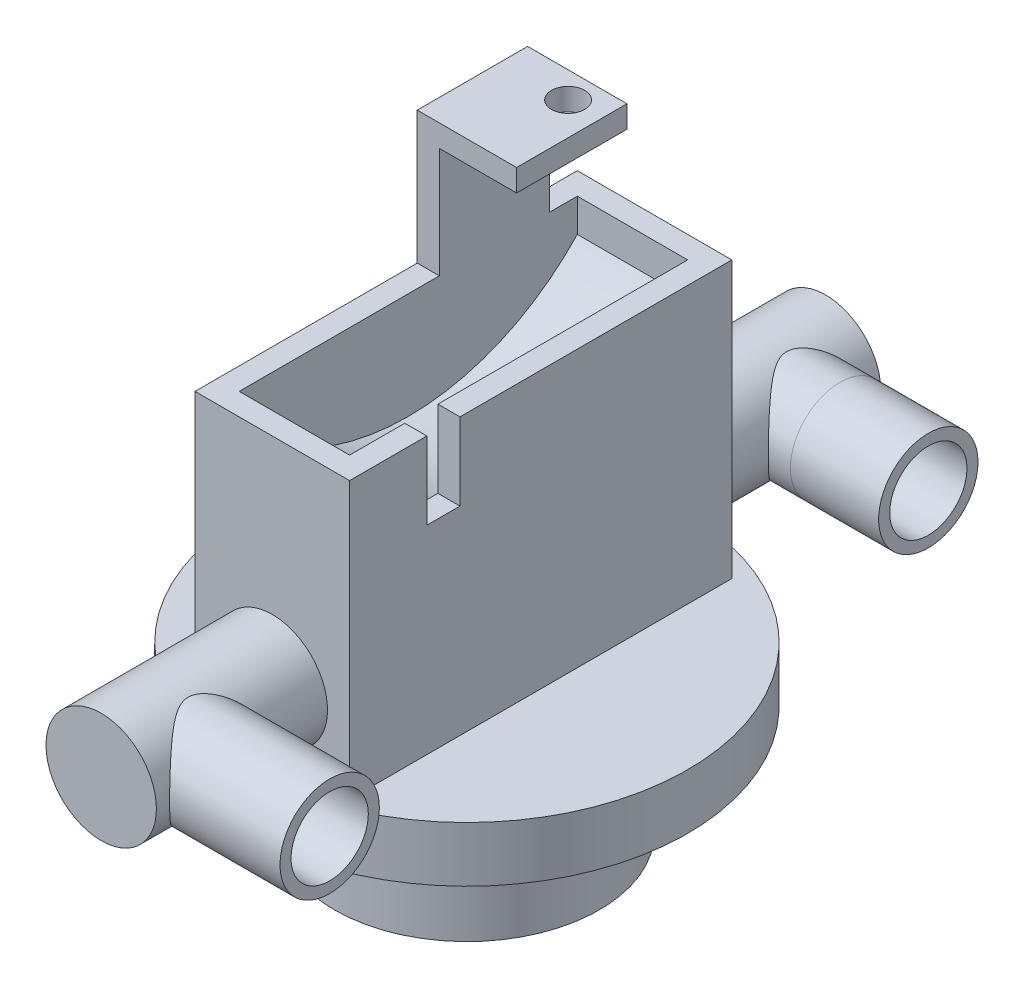
SolidWorks part; units mm, degrees
ref_plane "Спереди" through (0, 0, 0) normal (0, 0, 1) x (1, 0, 0)
ref_plane "Сверху" through (0, 0, 0) normal (0, 1, 0) x (1, 0, 0)
ref_plane "Справа" through (0, 0, 0) normal (1, 0, 0) x (0, 0, -1)
sketch "Эскиз1" plane through (0, 0, 0) normal (0, 1, 0) x (1, 0, 0)
  circle A0 centre (0, 0) radius 20
extrude "Бобышка-Вытянуть1" add sketch "Эскиз1" along normal blind 5 contours A0
sketch "Эскиз2" plane through (0, 5, 0) normal (0, 1, 0) x (1, 0, 0)
  line L0 (0, 20) -> (0, -20) construction
  line L1 (-20, 0) -> (20, 0) construction
  line L3 (-7, 17) -> (7, 17)
  line L4 (-7, 17) -> (-7, -17.63)
  line L5 (-7, -17.63) -> (7, -17.63)
  line L6 (7, 17) -> (7, -17.63)
  circle A0 centre (0, 0) radius 20 construction
  dimension "D1" = 7
  dimension "D2" = 14
  dimension "D3" = 17
  dimension "D4" = 7
  dimension "D5" = 20
extrude "Бобышка-Вытянуть2" add sketch "Эскиз2" along normal blind 25
sketch "Эскиз3" plane through (0, 30, 0) normal (0, 1, 0) x (1, 0, 0)
  line L0 (0, 17) -> (0, -17.63) construction
  line L1 (7, 17) -> (-7, 17) construction
  line L2 (-7, -17.63) -> (7, -17.63) construction
  line L3 (-7, -0.315) -> (7, -0.315) construction
  line L4 (-7, 17) -> (-7, -17.63) construction
  line L5 (7, -17.63) -> (7, 17) construction
  line L6 (-7, 17) -> (7, -17.63) construction
  line L7 (7, 17) -> (-7, -17.63) construction
  line L8 (-7, 17) -> (-7, -17.63) construction
  line L9 (5, -15.63) -> (-5, -15.63)
  line L10 (5, -15.63) -> (5, 15)
  line L11 (5, 15) -> (-5, 15)
  line L12 (-5, -15.63) -> (-5, 15)
  line L13 (5, -15.63) -> (-5, 15) construction
  line L14 (5, 15) -> (-5, -15.63) construction
  point P20 (0, -0.315)
  dimension "D1" = 2
  dimension "D2" = 2
extrude "Вырез-Вытянуть1" cut sketch "Эскиз3" against normal blind 3
sketch "Эскиз4" plane through (-5, 0, 0) normal (1, 0, 0) x (0, 0, -1)
  line L0 (-15.63, 27) -> (15, 27)
  arc A0 (-15.63, 27) -> (15, 27) centre (-0.315, 41.3684) ccw
  dimension "D1" = 30.63
  dimension "D2" = 21
extrude "Вырез-Вытянуть2" cut sketch "Эскиз4" along normal blind 10
sketch "Эскиз5" plane through (0, 30, 0) normal (0, 1, 0) x (1, 0, 0)
  line L0 (5, -7.63) -> (7, -7.63)
  line L1 (5, 15) -> (5, -15.63) construction
  line L2 (7, -17.63) -> (7, 17) construction
  line L3 (5, -10.63) -> (7, -10.63)
  line L4 (5, -15.63) -> (5, 15) construction
  line L5 (7, -7.63) -> (7, -10.63)
  line L6 (5, -7.63) -> (5, -10.63)
  dimension "D1" = 3
  dimension "D2" = 5
extrude "Вырез-Вытянуть3" cut sketch "Эскиз5" against normal blind 7
sketch "Эскиз6" plane through (0, 30, 0) normal (0, 1, 0) x (1, 0, 0)
  line L0 (-7, 12.5) -> (-5, 12.5)
  line L1 (-7, 17) -> (-7, -17.63) construction
  line L2 (-5, 15) -> (-5, -15.63) construction
  line L3 (-7, 2.5) -> (-5, 2.5)
  line L4 (-5, -15.63) -> (-5, 15) construction
  line L5 (-7, 12.5) -> (-7, 2.5)
  line L6 (-5, 12.5) -> (-5, 2.5)
  dimension "D1" = 2.5
  dimension "D2" = 10
extrude "Бобышка-Вытянуть3" add sketch "Эскиз6" along normal blind 10
sketch "Эскиз7" plane through (0, 40, 0) normal (0, 1, 0) x (1, 0, 0)
  line L0 (-7, 12.5) -> (-5, 12.5)
  line L1 (2, 2.5) -> (-5, 2.5)
  line L2 (-5, 2.5) -> (-7, 2.5)
  line L3 (-7, 2.5) -> (-7, 12.5)
  line L4 (-5, 12.5) -> (2, 12.5)
  line L5 (2, 12.5) -> (2, 2.5)
  dimension "D1" = 7
extrude "Бобышка-Вытянуть4" add sketch "Эскиз7" along normal blind 2
sketch "Эскиз8" plane through (0, 42, 0) normal (0, 1, 0) x (1, 0, 0)
  circle A0 centre (-0.9704, 10.136) radius 1.5
extrude "Вырез-Вытянуть4" cut sketch "Эскиз8" against normal blind 2
sketch "Эскиз9" plane through (0, 0, 17.63) normal (0, 0, 1) x (1, 0, 0)
  line L0 (0, 30) -> (0, 5) construction
  line L1 (-7, 30) -> (7, 30) construction
  line L2 (-7, 5) -> (7, 5) construction
  circle A0 centre (0, 11) radius 4
  dimension "D1" = 6
extrude "Вырез-Вытянуть5" cut sketch "Эскиз9" against normal blind 35
sketch "Эскиз10" plane through (0, 0, 17.63) normal (0, 0, 1) x (1, 0, 0)
  circle A0 centre (0, 11) radius 5
  circle A1 centre (0, 11) radius 4
  dimension "D1" = 10
  dimension "D2" = 8
extrude "Бобышка-Вытянуть5" add sketch "Эскиз10" along normal blind 14.5
sketch "Эскиз11" plane through (7, 0, 0) normal (1, 0, 0) x (0, 0, -1)
  line L0 (-17.63, 11) -> (-32.13, 11) construction
  line L1 (-17.63, 16) -> (-17.63, 6) construction
  line L2 (-32.13, 16) -> (-32.13, 6) construction
  line L3 (-17.63, 11) -> (33.3414, 11) construction
  line L4 (17, 30) -> (17, 5) construction
  circle A0 centre (-27.43, 11) radius 4.5
  circle A1 centre (26.8, 11) radius 4.5
  dimension "D1" = 9.8
  dimension "D2" = 9.8
extrude "Бобышка-Вытянуть6" add sketch "Эскиз11" against normal up to surface (2 mm away) up to face at (5, 11, 32.13)
sketch "Эскиз12" plane through (7, 0, 0) normal (1, 0, 0) x (0, 0, -1)
  circle A0 centre (-27.43, 11) radius 3.5
extrude "Вырез-Вытянуть6" cut sketch "Эскиз12" against normal up to next
sketch "Эскиз13" plane through (0, 0, 32.13) normal (0, 0, 1) x (1, 0, 0)
  circle A0 centre (0, 11) radius 5
extrude "Бобышка-Вытянуть7" add sketch "Эскиз13" along normal blind 1
sketch "Эскиз14" plane through (7, 0, 0) normal (1, 0, 0) x (0, 0, -1)
  circle A0 centre (-27.43, 11) radius 3.5
  circle A1 centre (-27.43, 11) radius 4.5
  circle A2 centre (26.8, 11) radius 3.5
  circle A3 centre (26.8, 11) radius 4.5
extrude "Бобышка-Вытянуть8" add sketch "Эскиз14" along normal blind 8
sketch "Эскиз15" plane through (0, 0, -17) normal (0, 0, -1) x (-1, 0, 0)
  circle A0 centre (0, 11) radius 3.998
  circle A1 centre (0, 11) radius 5
extrude "Бобышка-Вытянуть9" add sketch "Эскиз15" along normal blind 14.5
sketch "Эскиз16" plane through (0, 0, -31.5) normal (0, 0, -1) x (-1, 0, 0)
  circle A1 centre (0, 11) radius 5
extrude "Бобышка-Вытянуть11" add sketch "Эскиз16" along normal blind 1
sketch "Эскиз17" plane through (7, 0, 0) normal (1, 0, 0) x (0, 0, -1)
  circle A0 centre (26.8, 11) radius 3.5
extrude "Вырез-Вытянуть7" cut sketch "Эскиз17" against normal up to next
sketch "Эскиз19" plane through (0, 0, 0) normal (0, -1, 0) x (1, 0, 0)
  circle A0 centre (0, 0) radius 12
extrude "Бобышка-Вытянуть12" add sketch "Эскиз19" along normal blind 10
